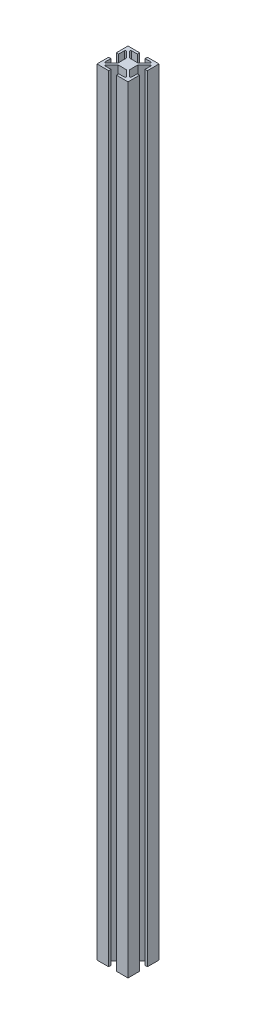
SolidWorks part; units mm, degrees
ref_plane "Plan de face" through (0, 0, 0) normal (0, 0, 1) x (1, 0, 0)
ref_plane "Plan de dessus" through (0, 0, 0) normal (0, 1, 0) x (1, 0, 0)
ref_plane "Plan de droite" through (0, 0, 0) normal (1, 0, 0) x (0, 0, -1)
sketch "Esquisse1" plane through (0, 0, 0) normal (0, 1, 0) x (1, 0, 0)
  line L0 (6.1245, 16.1036) -> (30.6226, 16.1036) construction
  line L6 (-11.5924, 0) -> (12.1076, 0) construction
  line L7 (0, 12.3466) -> (0, -12.7449) construction
  line L12 (-10, -10) -> (10, 10) construction
  line L59 (-10, -2.5) -> (-10, -10)
  line L60 (-10, -2.5) -> (-8.5, -2.5)
  line L69 (-8.5, -2.5) -> (-8.5, -6.2322)
  line L70 (-7.6464, -6.5858) -> (-3.75, -2.6893)
  line L73 (-6.5858, -7.6464) -> (-2.6893, -3.75)
  line L74 (-2.5, -8.5) -> (-6.2322, -8.5)
  line L75 (-2.5, -10) -> (-2.5, -8.5)
  line L76 (-2.5, -10) -> (-10, -10)
  line L77 (-2.5, 10) -> (-2.5, 8.5)
  line L78 (-2.5, 10) -> (-10, 10)
  line L79 (-10, 2.5) -> (-10, 10)
  line L80 (-10, 2.5) -> (-8.5, 2.5)
  line L81 (-8.5, 2.5) -> (-8.5, 6.2322)
  line L82 (-7.6464, 6.5858) -> (-3.75, 2.6893)
  line L83 (-6.5858, 7.6464) -> (-2.6893, 3.75)
  line L84 (-2.5, 8.5) -> (-6.2322, 8.5)
  line L85 (10, 2.5) -> (8.5, 2.5)
  line L86 (10, 2.5) -> (10, 10)
  line L87 (2.5, 10) -> (10, 10)
  line L88 (2.5, 10) -> (2.5, 8.5)
  line L89 (2.5, 8.5) -> (6.2322, 8.5)
  line L90 (6.5858, 7.6464) -> (2.6893, 3.75)
  line L91 (7.6464, 6.5858) -> (3.75, 2.6893)
  line L92 (8.5, 2.5) -> (8.5, 6.2322)
  line L93 (2.5, -10) -> (2.5, -8.5)
  line L94 (2.5, -10) -> (10, -10)
  line L95 (10, -2.5) -> (10, -10)
  line L96 (10, -2.5) -> (8.5, -2.5)
  line L97 (8.5, -2.5) -> (8.5, -6.2322)
  line L98 (7.6464, -6.5858) -> (3.75, -2.6893)
  line L99 (6.5858, -7.6464) -> (2.6893, -3.75)
  line L100 (2.5, -8.5) -> (6.2322, -8.5)
  line L101 (-3.75, 2.6893) -> (-3.75, -2.6893)
  line L102 (-2.6893, -3.75) -> (2.6893, -3.75)
  line L103 (-2.6893, 3.75) -> (2.6893, 3.75)
  line L104 (3.75, 2.6893) -> (3.75, -2.6893)
  arc A0 (-8.5, 6.2322) -> (-7.6464, 6.5858) centre (-8, 6.2322) cw
  arc A1 (-8.5, -6.2322) -> (-7.6464, -6.5858) centre (-8, -6.2322) ccw
  arc A2 (-6.5858, -7.6464) -> (-6.2322, -8.5) centre (-6.2322, -8) ccw
  arc A3 (6.5858, -7.6464) -> (6.2322, -8.5) centre (6.2322, -8) cw
  arc A4 (8.5, -6.2322) -> (7.6464, -6.5858) centre (8, -6.2322) cw
  arc A5 (7.6464, 6.5858) -> (8.5, 6.2322) centre (8, 6.2322) cw
  arc A6 (6.2322, 8.5) -> (6.5858, 7.6464) centre (6.2322, 8) cw
  arc A7 (-6.5858, 7.6464) -> (-6.2322, 8.5) centre (-6.2322, 8) cw
  point P7 (-2.5, -9.25)
  point P8 (2.5, -9.25)
  point P15 (-8.5, -7.4393)
  point P51 (0, 0)
  point P52 (-7.4393, -8.5)
  dimension "D2" = 5
  dimension "D7" = 0.5
  dimension "D1" = 20
  dimension "D3" = 4
  dimension "D4" = 7.5
  dimension "D5" = 1.5
  dimension "D6" = 1.5
extrude "Boss.-Extru.1" add sketch "Esquisse1" along normal blind 500
